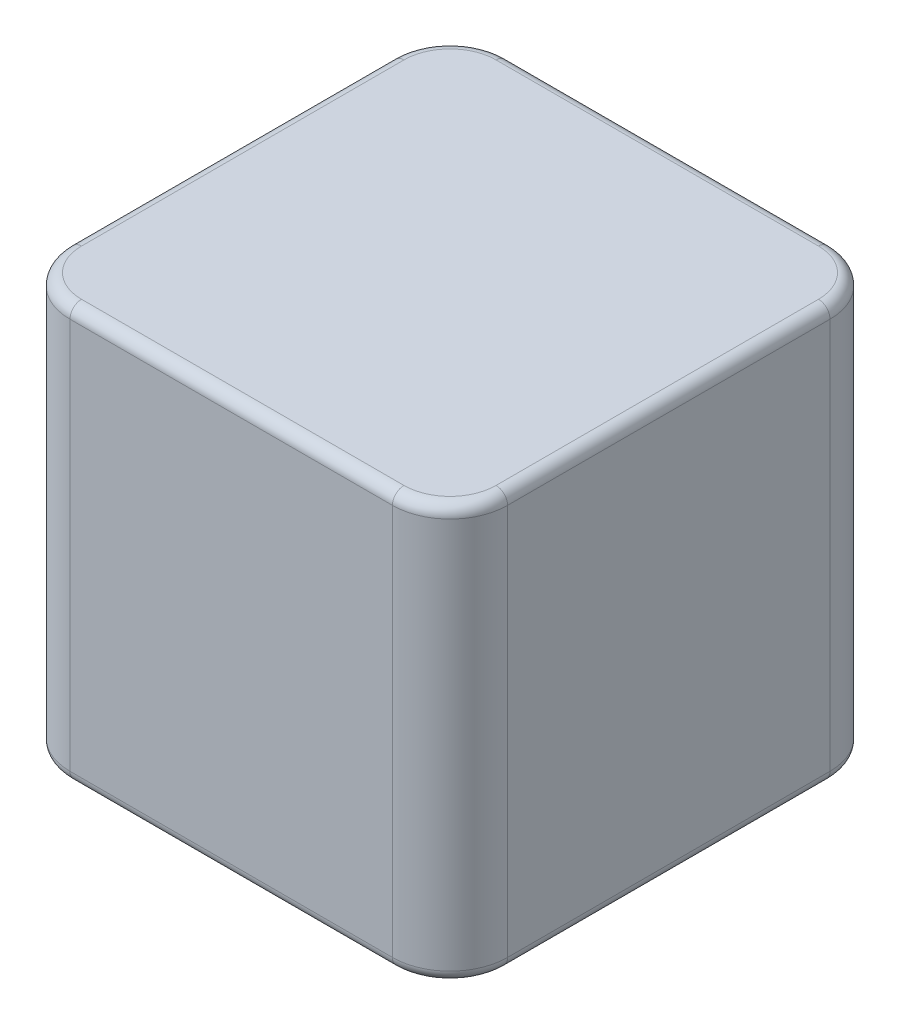
SolidWorks part; units mm, degrees
ref_plane "Front Plane" through (0, 0, 0) normal (0, 0, 1) x (1, 0, 0)
ref_plane "Top Plane" through (0, 0, 0) normal (0, 1, 0) x (1, 0, 0)
ref_plane "Right Plane" through (0, 0, 0) normal (1, 0, 0) x (0, 0, -1)
sketch "Sketch1" plane through (0, 0, 0) normal (0, 1, 0) x (1, 0, 0)
  line L1 (-19, -19) -> (19, -19)
  line L2 (-19, -19) -> (-19, 19)
  line L3 (-19, 19) -> (19, 19)
  line L4 (19, -19) -> (19, 19)
  line L5 (-19, -19) -> (19, 19) construction
  line L6 (-19, 19) -> (19, -19) construction
  point P0 (0, 0)
extrude "Boss-Extrude1" add sketch "Sketch1" along normal blind 36
sketch "Sketch3" plane through (0, 0, 0) normal (0, -1, 0) x (1, 0, 0)
  circle A0 centre (0, 0) radius 7
extrude "Cut-Extrude1" cut sketch "Sketch3" against normal blind 2
fillet "Fillet1" radius 5 4 edges at (19, 18, -19) (19, 18, 19) (-19, 18, -19) (-19, 18, 19)
fillet "Fillet2" radius 1 16 edges at (-17.5355, 0, 17.5355) (-19, 0, 0) (-17.5355, 0, -17.5355) (0, 0, -19) (17.5355, 0, -17.5355) (19, 0, 0) (17.5355, 0, 17.5355) (-17.5355, 36, 17.5355) (-19, 36, 0) (-17.5355, 36, -17.5355) (0, 36, -19) (17.5355, 36, -17.5355) (19, 36, 0) (17.5355, 36, 17.5355) (0, 0, 19) (0, 36, 19)
